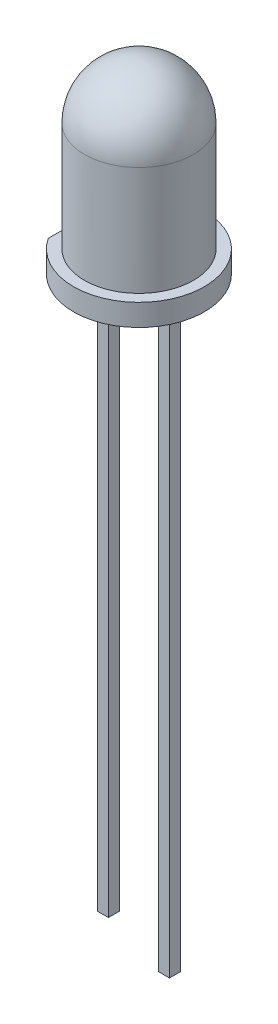
SolidWorks part; units mm, degrees
ref_plane "Front Plane" through (0, 0, 0) normal (0, 0, 1) x (1, 0, 0)
ref_plane "Top Plane" through (0, 0, 0) normal (0, 1, 0) x (1, 0, 0)
ref_plane "Right Plane" through (0, 0, 0) normal (1, 0, 0) x (0, 0, -1)
sketch "Sketch1" plane through (0, 0, 0) normal (0, 1, 0) x (1, 0, 0)
  line L0 (-2.5, 1.6583) -> (-2.5, -1.6583)
  arc A0 (-2.5, -1.6583) -> (-2.5, 1.6583) centre (0, 0) ccw
  dimension "D1" = 6
  dimension "D2" = 2.5
extrude "Boss-Extrude1" add sketch "Sketch1" along normal blind 1
sketch "Sketch2" plane through (0, 1, 0) normal (0, 1, 0) x (1, 0, 0)
  circle A0 centre (0, 0) radius 2.5
  dimension "D1" = 5
extrude "Boss-Extrude2" add sketch "Sketch2" along normal blind 7.5
fillet "Fillet1" radius 2.5 1 edges at (0, 8.5, 2.5)
sketch "Sketch3" plane through (0, 0, 0) normal (0, 1, 0) x (1, 0, 0)
  line L0 (0, -3.3) -> (0, 3.3) construction
  line L1 (-1.65, 0.25) -> (-1.15, 0.25)
  line L2 (-1.65, 0.25) -> (-1.65, -0.25)
  line L3 (-1.65, -0.25) -> (-1.15, -0.25)
  line L4 (-1.15, 0.25) -> (-1.15, -0.25)
  line L5 (-1.65, 0.25) -> (-1.15, -0.25) construction
  line L6 (-1.65, -0.25) -> (-1.15, 0.25) construction
  line L7 (1.65, -0.25) -> (1.15, -0.25)
  line L8 (1.15, 0.25) -> (1.15, -0.25)
  line L9 (1.65, 0.25) -> (1.15, 0.25)
  line L10 (1.65, 0.25) -> (1.65, -0.25)
  point P0 (-1.4, 0)
  point P5 (0, 0)
  point P10 (0, 0)
  dimension "D1" = 1.4
  dimension "D2" = 0.5
extrude "Boss-Extrude3" add sketch "Sketch3" against normal blind 26
sketch "Sketch4" plane through (0, -26, 0) normal (0, -1, 0) x (1, 0, 0)
  line L1 (1.15, -0.25) -> (1.65, -0.25)
  line L2 (1.15, -0.25) -> (1.15, 0.25)
  line L3 (1.15, 0.25) -> (1.65, 0.25)
  line L4 (1.65, -0.25) -> (1.65, 0.25)
extrude "Boss-Extrude4" add sketch "Sketch4" along normal blind 1
